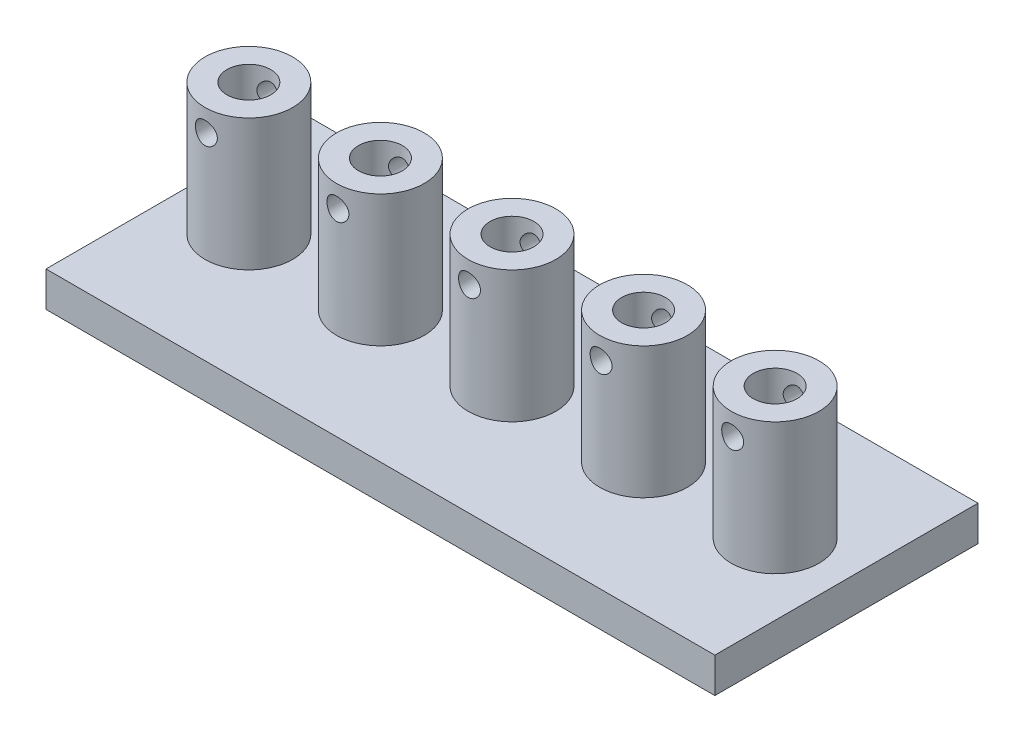
SolidWorks part; units mm, degrees
ref_plane "Front Plane" through (0, 0, 0) normal (0, 0, 1) x (1, 0, 0)
ref_plane "Top Plane" through (0, 0, 0) normal (0, 1, 0) x (1, 0, 0)
ref_plane "Right Plane" through (0, 0, 0) normal (1, 0, 0) x (0, 0, -1)
sketch "Sketch1" plane through (0, 0, 0) normal (0, 1, 0) x (1, 0, 0)
  line L1 (-15.25, 6) -> (15.25, 6)
  line L2 (-15.25, 6) -> (-15.25, -6)
  line L3 (-15.25, -6) -> (15.25, -6)
  line L4 (15.25, 6) -> (15.25, -6)
  line L5 (-15.25, 6) -> (15.25, -6) construction
  line L6 (-15.25, -6) -> (15.25, 6) construction
  point P0 (0, 0)
  dimension "D1" = 12
  dimension "D2" = 30.5
extrude "Boss-Extrude1" add sketch "Sketch1" along normal blind 1.6
sketch "Sketch2" plane through (0, 1.6, 0) normal (0, 1, 0) x (1, 0, 0)
  line L0 (0, 0) -> (6, 0) construction
  line L1 (0, 0) -> (-6, 0) construction
  line L2 (-12, 0) -> (-6, 0) construction
  circle A0 centre (0, 0) radius 2
  circle A1 centre (6, 0) radius 2
  circle A2 centre (12, 0) radius 2
  circle A3 centre (-6, 0) radius 2
  circle A4 centre (-12, 0) radius 2
  circle A5 centre (-12, 0) radius 1
  circle A6 centre (-6, 0) radius 1
  circle A7 centre (0, 0) radius 1
  circle A8 centre (6, 0) radius 1
  circle A9 centre (12, 0) radius 1
  dimension "D1" = 4
  dimension "D6" = 2
  dimension "D3" = 6
  dimension "D5" = 6
  dimension "D8" = 6
  dimension "D2" = 3
  dimension "D4" = 3
  dimension "D7" = 5
extrude "Boss-Extrude2" add sketch "Sketch2" along normal blind 6
sketch "Sketch3" plane through (0, 0, 0) normal (0, 0, 1) x (1, 0, 0)
  line L0 (-12, 7.6) -> (-12, 6.6) construction
  line L1 (-10, 7.6) -> (-14, 7.6) construction
  circle A0 centre (-12, 6.6) radius 0.5
  circle A1 centre (-6, 6.6) radius 0.5
  circle A2 centre (0, 6.6) radius 0.5
  circle A3 centre (6, 6.6) radius 0.5
  circle A4 centre (12, 6.6) radius 0.5
  dimension "D2" = 1
  dimension "D1" = 1
extrude "Cut-Extrude1" cut sketch "Sketch3" against normal blind 2 and the other way blind 2
